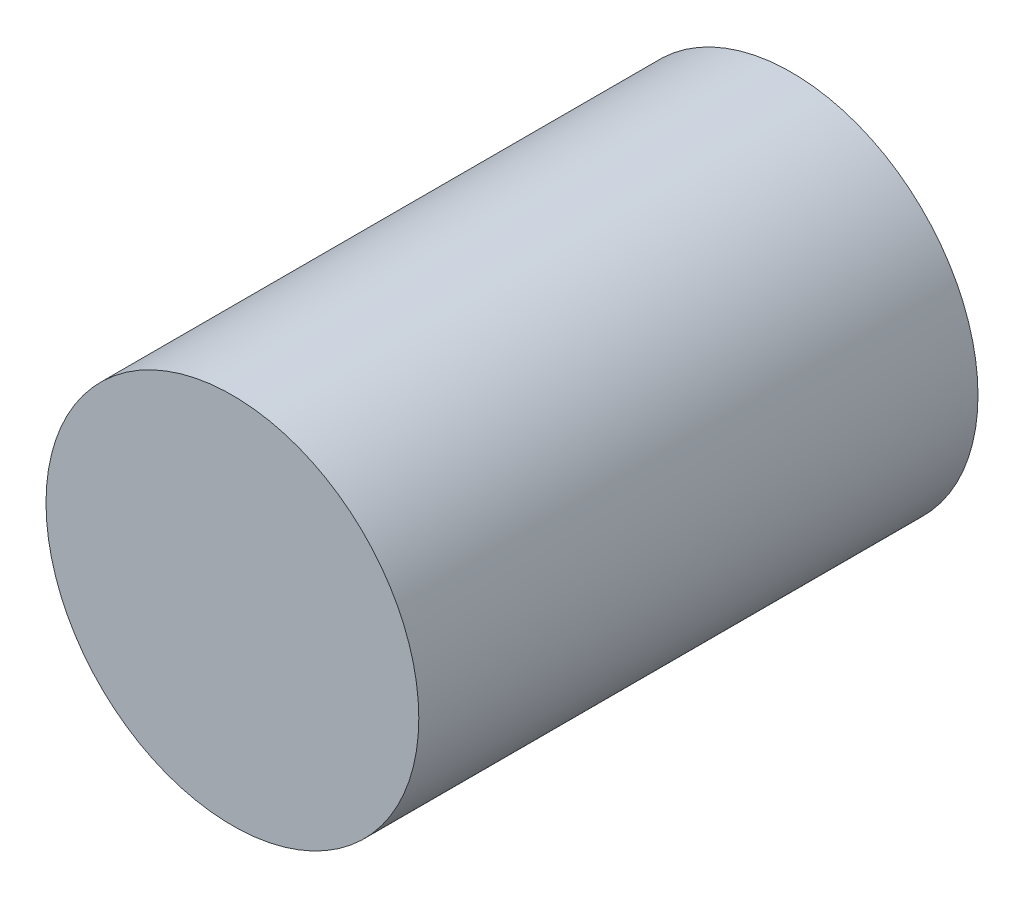
SolidWorks part; units mm, degrees
ref_plane "Front Plane" through (0, 0, 0) normal (0, 0, 1) x (1, 0, 0)
ref_plane "Top Plane" through (0, 0, 0) normal (0, 1, 0) x (1, 0, 0)
ref_plane "Right Plane" through (0, 0, 0) normal (1, 0, 0) x (0, 0, -1)
sketch "Sketch1" plane through (0, 0, 0) normal (0, 0, 1) x (1, 0, 0)
  circle A0 centre (0, 0) radius 100
  dimension "D1" = 200
extrude "Boss-Extrude2" add sketch "Sketch1" along normal blind 300
